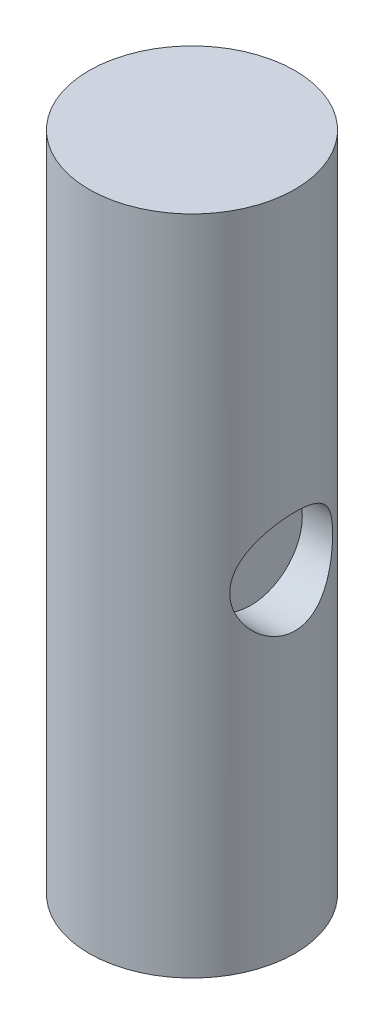
SolidWorks part; units mm, degrees
ref_plane "前视基准面" through (0, 0, 0) normal (0, 0, 1) x (1, 0, 0)
ref_plane "上视基准面" through (0, 0, 0) normal (0, 1, 0) x (1, 0, 0)
ref_plane "右视基准面" through (0, 0, 0) normal (1, 0, 0) x (0, 0, -1)
sketch "草图1" plane through (0, 0, 0) normal (0, 1, 0) x (1, 0, 0)
  circle A0 centre (0, 0) radius 7
extrude "凸台-拉伸1" add sketch "草图1" along normal blind 45
ref_plane "基准面2" through (15, 0, 0) normal (1, 0, 0) x (0, 0, -1)
sketch "草图4" plane through (15, 0, 0) normal (1, 0, 0) x (0, 0, -1)
  line L0 (-7, 22.5) -> (7, 22.5)
  line L1 (-7, 45) -> (-7, 0) construction
  line L2 (7, 0) -> (7, 45) construction
  circle A0 centre (0, 22.5) radius 3.5
extrude "切除-拉伸1" cut sketch "草图4" against normal blind 11 contours L0 A0 | L0 A0
ref_plane "基准面3" through (-15, 0, 0) normal (1, 0, 0) x (0, 0, -1)
sketch "草图5" plane through (-15, 0, 0) normal (1, 0, 0) x (0, 0, -1)
  line L0 (7, 22.5) -> (-7, 22.5)
  line L1 (7, 0) -> (7, 45) construction
  line L2 (-7, 45) -> (-7, 0) construction
  circle A0 centre (0, 22.5) radius 3.5
extrude "切除-拉伸2" cut sketch "草图5" along normal blind 11 contours L0 A0 | L0 A0
